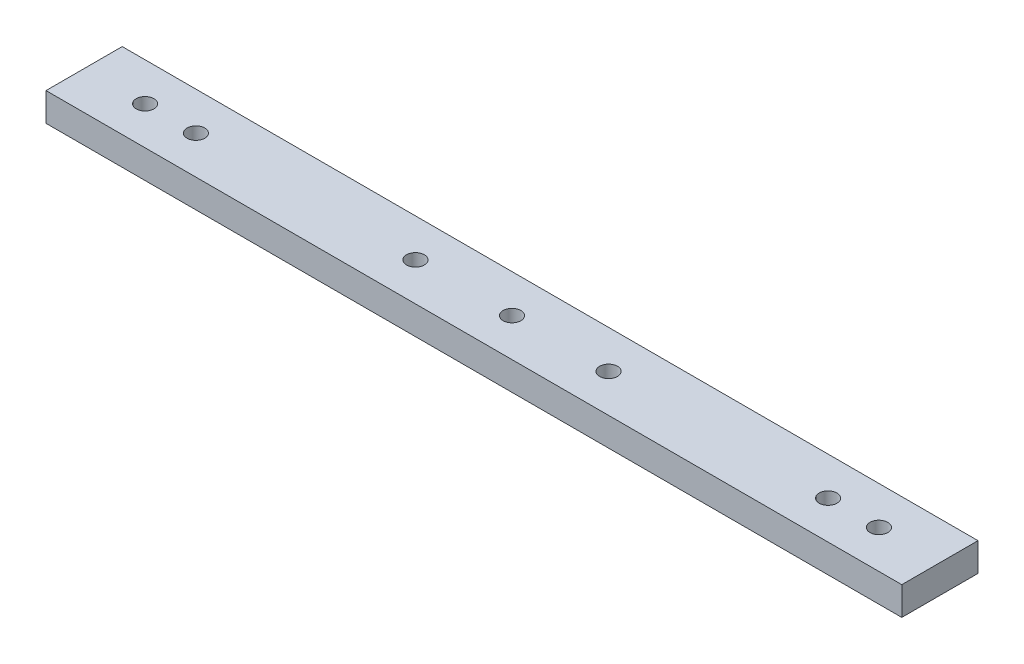
SolidWorks part; units mm, degrees
ref_plane "Front Plane" through (0, 0, 0) normal (0, 0, 1) x (1, 0, 0)
ref_plane "Top Plane" through (0, 0, 0) normal (0, 1, 0) x (1, 0, 0)
ref_plane "Right Plane" through (0, 0, 0) normal (1, 0, 0) x (0, 0, -1)
sketch "Sketch1" plane through (0, 0, 0) normal (0, 1, 0) x (1, 0, 0)
  line L1 (-71.3549, -2.9708) -> (97.0571, -2.9708)
  line L2 (-71.3549, -2.9708) -> (-71.3549, 12.0292)
  line L3 (-71.3549, 12.0292) -> (97.0571, 12.0292)
  line L4 (97.0571, -2.9708) -> (97.0571, 12.0292)
  dimension "D1" = 168.412
  dimension "D2" = 15
extrude "Boss-Extrude1" add sketch "Sketch1" along normal blind 5.588
sketch "Sketch2" plane through (0, 5.588, 0) normal (0, 1, 0) x (1, 0, 0)
  line L0 (-71.3549, 4.5292) -> (97.0571, 4.5292) construction
  line L1 (-71.3549, 12.0292) -> (-71.3549, -2.9708) construction
  line L2 (97.0571, -2.9708) -> (97.0571, 12.0292) construction
  line L3 (12.8511, -2.9708) -> (12.8511, 12.0292) construction
  line L4 (-71.3549, -2.9708) -> (97.0571, -2.9708) construction
  line L5 (97.0571, 12.0292) -> (-71.3549, 12.0292) construction
  circle A0 centre (-59.3549, 4.5292) radius 1.75
  circle A1 centre (-49.3549, 4.5292) radius 1.75
  circle A2 centre (75.0571, 4.5292) radius 1.75
  circle A3 centre (85.0571, 4.5292) radius 1.75
  dimension "D1" = 3.5
  dimension "D2" = 10
  dimension "D3" = 12
extrude "Cut-Extrude1" cut sketch "Sketch2" against normal through all
sketch "Sketch3" plane through (0, 5.588, 0) normal (0, 1, 0) x (1, 0, 0)
  line L0 (-71.3549, 4.5292) -> (97.0571, 4.5292) construction
  line L1 (-71.3549, 12.0292) -> (-71.3549, -2.9708) construction
  line L2 (97.0571, -2.9708) -> (97.0571, 12.0292) construction
  line L3 (12.8511, -2.9708) -> (12.8511, 12.0292) construction
  line L4 (-71.3549, -2.9708) -> (97.0571, -2.9708) construction
  line L5 (97.0571, 12.0292) -> (-71.3549, 12.0292) construction
  circle A0 centre (-6.1489, 4.5292) radius 1.75
  circle A1 centre (31.8511, 4.5292) radius 1.75
  circle A2 centre (12.8511, 4.5292) radius 1.75
  dimension "D1" = 3.5
  dimension "D2" = 38
extrude "Cut-Extrude2" cut sketch "Sketch3" against normal through all
